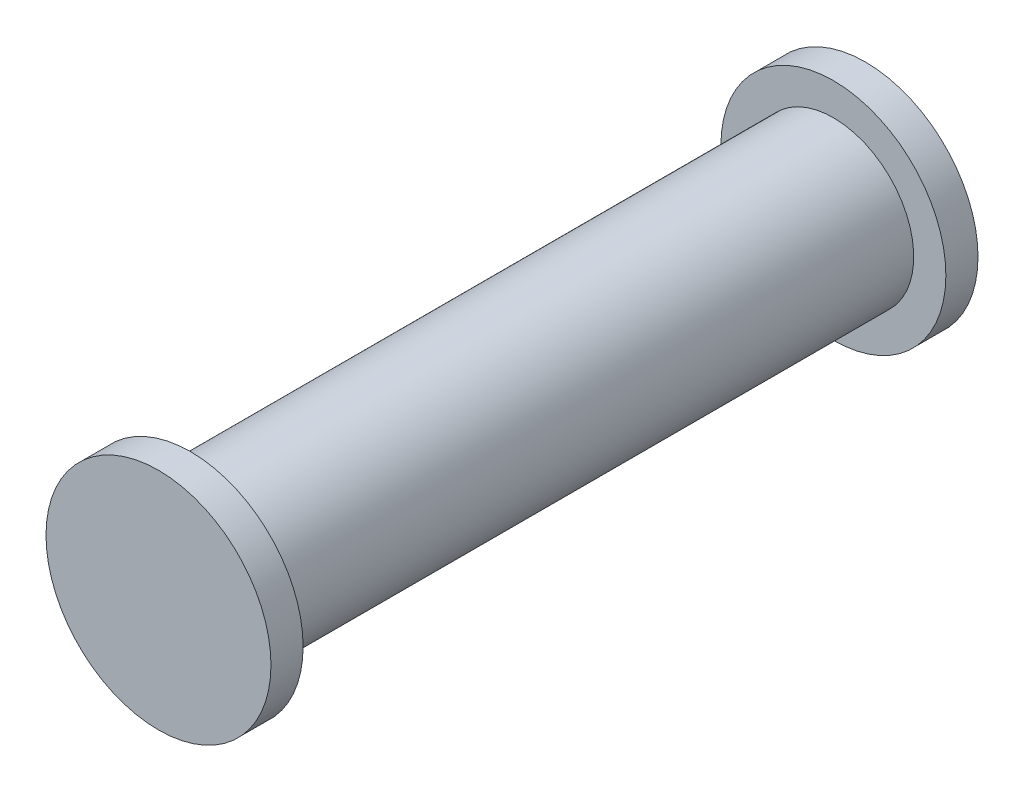
SolidWorks part; units mm, degrees
ref_plane "前视基准面" through (0, 0, 0) normal (0, 0, 1) x (1, 0, 0)
ref_plane "上视基准面" through (0, 0, 0) normal (0, 1, 0) x (1, 0, 0)
ref_plane "右视基准面" through (0, 0, 0) normal (1, 0, 0) x (0, 0, -1)
sketch "草图1" plane through (0, 0, 0) normal (0, 0, 1) x (1, 0, 0)
  circle A0 centre (0, 0) radius 5
extrude "凸台-拉伸1" add sketch "草图1" along normal blind 42
sketch "草图3" plane through (0, 0, 0) normal (0, 0, -1) x (-1, 0, 0)
  circle A0 centre (0, 0) radius 5
extrude "拉伸-薄壁2" add sketch "草图3" against normal blind 2 thin
sketch "草图4" plane through (0, 0, 42) normal (0, 0, 1) x (1, 0, 0)
  circle A0 centre (0, 0) radius 5
extrude "拉伸-薄壁4" add sketch "草图4" along normal blind 2 separate body thin
sketch "草图5" plane through (0, 0, 42) normal (0, 0, 1) x (1, 0, 0)
  circle A0 centre (0, 0) radius 5
extrude "凸台-拉伸2" add sketch "草图5" along normal blind 2
